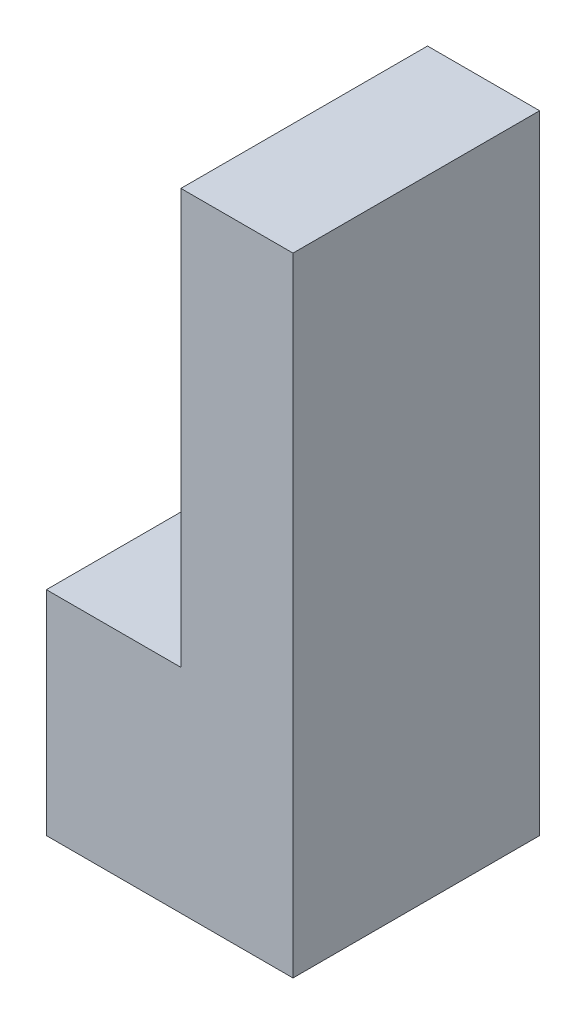
SolidWorks part; units mm, degrees
material "Pine"
ref_plane "Front Plane" through (0, 0, 0) normal (0, 0, 1) x (1, 0, 0)
ref_plane "Top Plane" through (0, 0, 0) normal (0, 1, 0) x (1, 0, 0)
ref_plane "Right Plane" through (0, 0, 0) normal (1, 0, 0) x (0, 0, -1)
sketch "Sketch1" plane through (0, 0, 0) normal (0, 1, 0) x (1, 0, 0)
  line L1 (-371.9573, 434.6222) -> (-232.2573, 434.6222)
  line L2 (-371.9573, 434.6222) -> (-371.9573, 294.9222)
  line L3 (-371.9573, 294.9222) -> (-232.2573, 294.9222)
  line L4 (-232.2573, 434.6222) -> (-232.2573, 294.9222)
  dimension "D1" = 139.7
  dimension "D2" = 139.7
extrude "Boss-Extrude1" add sketch "Sketch1" along normal blind 355.6
sketch "Sketch3" plane through (0, 355.6, 0) normal (0, 1, 0) x (1, 0, 0)
  line L0 (-371.9573, 294.9222) -> (-232.2573, 294.9222) construction
  line L1 (-371.9573, 434.6222) -> (-295.7573, 434.6222)
  line L2 (-371.9573, 434.6222) -> (-371.9573, 294.9222)
  line L3 (-371.9573, 294.9222) -> (-295.7573, 294.9222)
  line L4 (-295.7573, 434.6222) -> (-295.7573, 294.9222)
  dimension "D1" = 76.2
extrude "Cut-Extrude1" cut sketch "Sketch3" against normal blind 234.95
